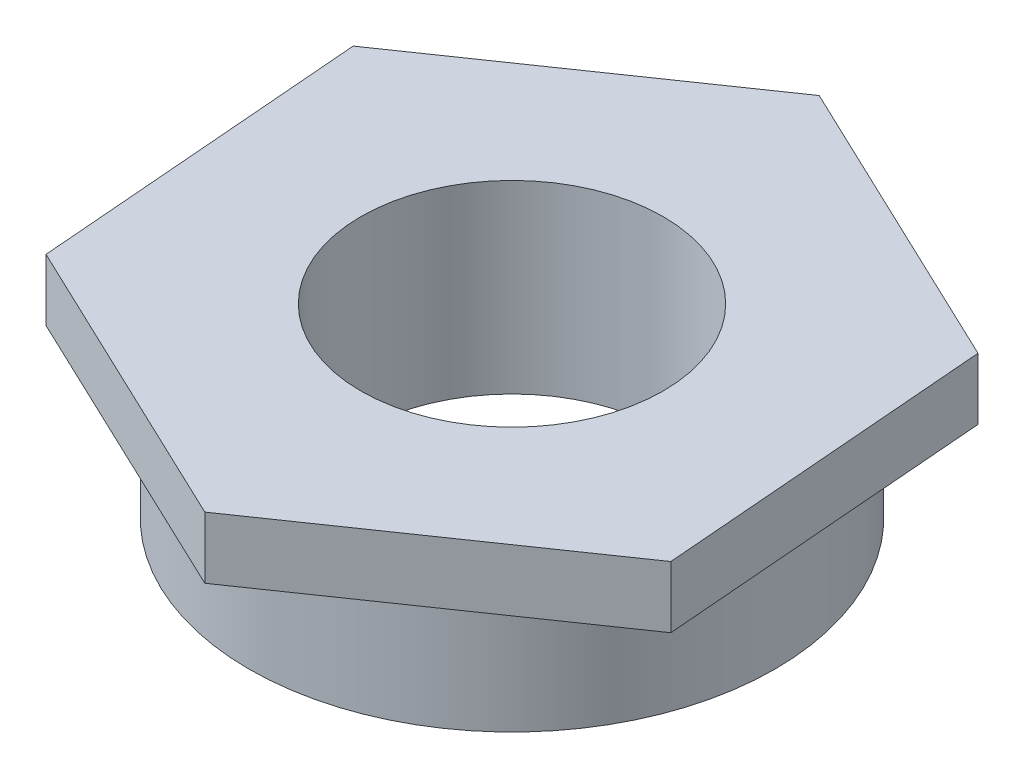
SolidWorks part; units mm, degrees
ref_plane "前视基准面" through (0, 0, 0) normal (0, 0, 1) x (1, 0, 0)
ref_plane "上视基准面" through (0, 0, 0) normal (0, 1, 0) x (1, 0, 0)
ref_plane "右视基准面" through (0, 0, 0) normal (1, 0, 0) x (0, 0, -1)
sketch "草图1" plane through (0, 0, 0) normal (0, 1, 0) x (1, 0, 0)
  line L1 (2.5031, -1.1893) -> (2.2815, 1.5731)
  line L2 (2.2815, 1.5731) -> (-0.2216, 2.7624)
  line L3 (-0.2216, 2.7624) -> (-2.5031, 1.1893)
  line L4 (-2.5031, 1.1893) -> (-2.2815, -1.5731)
  line L5 (-2.2815, -1.5731) -> (0.2216, -2.7624)
  line L6 (0.2216, -2.7624) -> (2.5031, -1.1893)
  circle A0 centre (0, 0) radius 2.4 construction
  dimension "D1" = 4.8
extrude "凸台-拉伸1" add sketch "草图1" along normal blind 0.51
sketch "草图2" plane through (0, 0, 0) normal (0, -1, 0) x (1, 0, 0)
  circle A0 centre (0, 0) radius 2.175
extrude "凸台-拉伸2" add sketch "草图2" along normal blind 1.02 contours A0
sketch "草图3" plane through (0, -1.02, 0) normal (0, -1, 0) x (-1, 0, 0)
  circle A0 centre (0, 0) radius 1.25
extrude "切除-拉伸1" cut sketch "草图3" against normal through all
